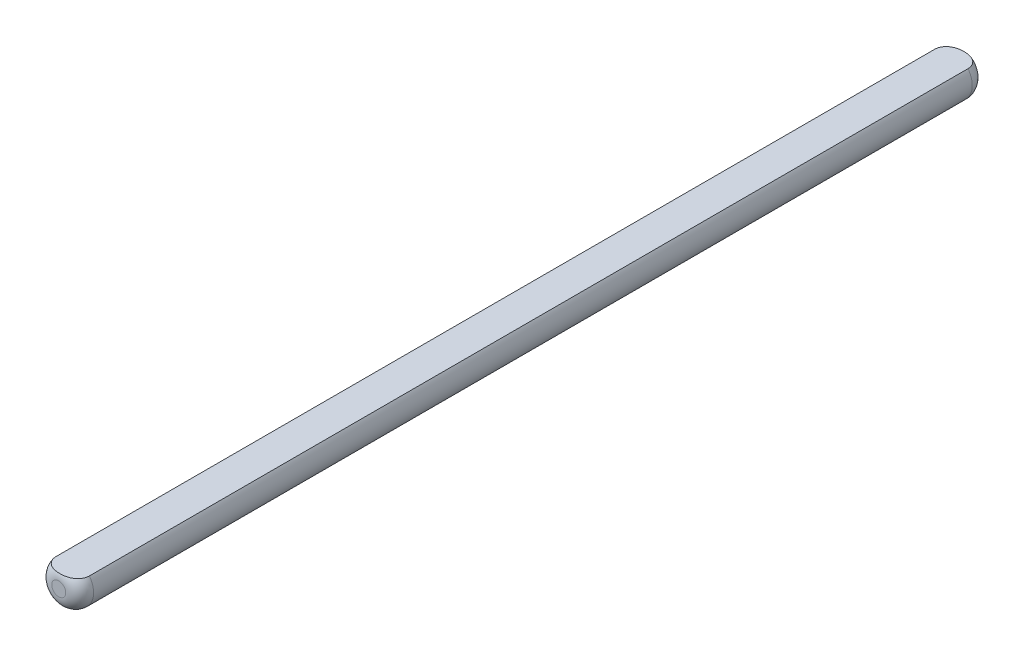
SolidWorks part; units mm, degrees
ref_plane "Plan de face" through (0, 0, 0) normal (0, 0, 1) x (1, 0, 0)
ref_plane "Plan de dessus" through (0, 0, 0) normal (0, 1, 0) x (1, 0, 0)
ref_plane "Plan de droite" through (0, 0, 0) normal (1, 0, 0) x (0, 0, -1)
sketch "Esquisse1" plane through (0, 0, 0) normal (0, 0, 1) x (1, 0, 0)
  circle A0 centre (0, 0) radius 3
  dimension "D1" = 6
extrude "Boss.-Extru.1" add sketch "Esquisse1" along normal blind 130
fillet "Congé1" radius 2 2 edges at (3, 0, 0) (3, 0, 130)
sketch "Esquisse2" plane through (0, 0, 130) normal (0, 0, 1) x (1, 0, 0)
  line L1 (-3, 3) -> (3, 3)
  line L2 (-3, 3) -> (-3, 1.8)
  line L3 (-3, 1.8) -> (3, 1.8)
  line L4 (3, 3) -> (3, 1.8)
  circle A0 centre (0, 0) radius 3 construction
  point P6 (0, 3)
  dimension "D1" = 6
  dimension "D2" = 1.2
extrude "Enlèv. mat.-Extru.1" cut sketch "Esquisse2" against normal through all
sketch "Esquisse3" plane through (0, 0, 0) normal (0, 0, -1) x (-1, 0, 0)
  point P0 (0, 0)
